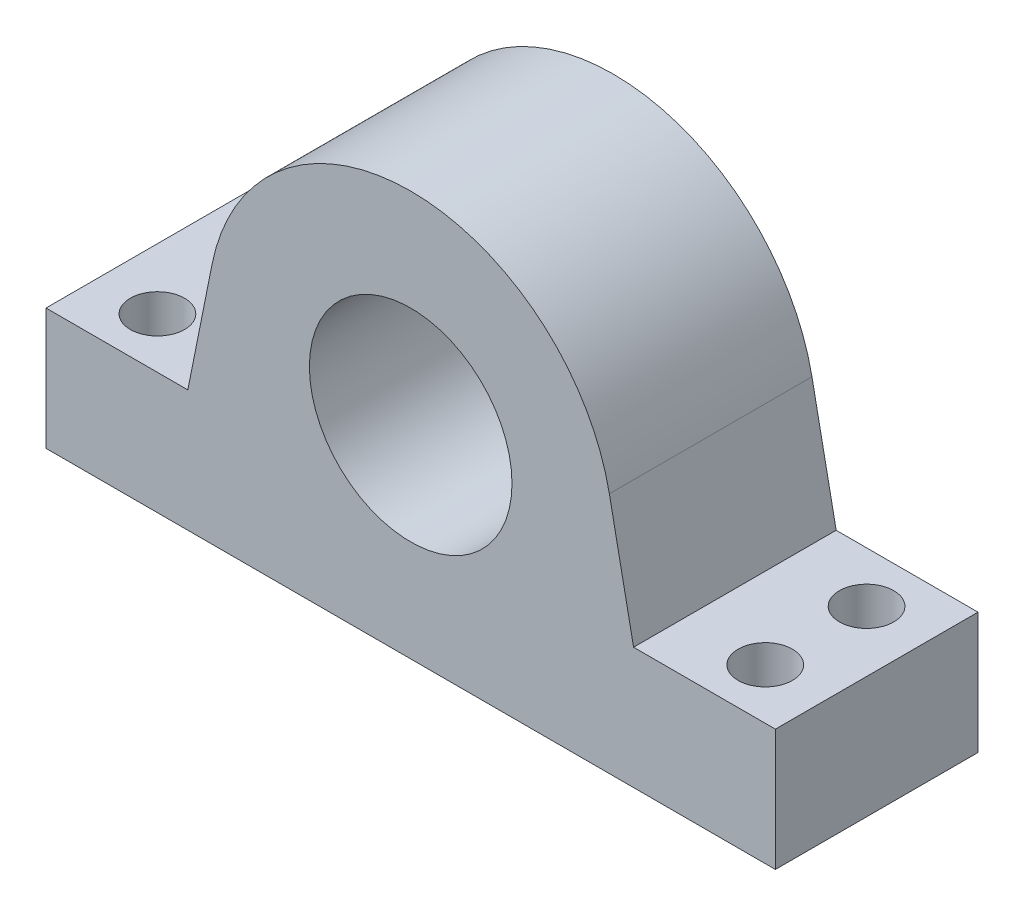
SolidWorks part; units mm, degrees
ref_plane "Front Plane" through (0, 0, 0) normal (0, 0, 1) x (1, 0, 0)
ref_plane "Top Plane" through (0, 0, 0) normal (0, 1, 0) x (1, 0, 0)
ref_plane "Right Plane" through (0, 0, 0) normal (1, 0, 0) x (0, 0, -1)
sketch "Sketch1" plane through (0, 0, 0) normal (0, 0, 1) x (1, 0, 0)
  line L0 (-12.4526, 2.4946) -> (-13.97, -5.08)
  line L1 (12.4526, 2.4946) -> (13.97, -5.08)
  line L2 (-13.97, -5.08) -> (-22.86, -5.08)
  line L3 (-22.86, -5.08) -> (-22.86, -12.7)
  line L4 (-22.86, -12.7) -> (22.86, -12.7)
  line L5 (22.86, -12.7) -> (22.86, -5.08)
  line L6 (22.86, -5.08) -> (13.97, -5.08)
  circle A0 centre (0, 0) radius 6.35
  arc A1 (12.4526, 2.4946) -> (-12.4526, 2.4946) centre (0, 0) ccw
  point P8 (0, 0)
  dimension "D1" = 12.7
  dimension "D6" = 12.7
  dimension "D2" = 7.62
  dimension "D3" = 45.72
  dimension "D4" = 12.7
  dimension "D5" = 8.89
extrude "Boss-Extrude1" add sketch "Sketch1" along normal mid plane 12.7
sketch "Sketch2" plane through (0, -5.08, 0) normal (0, 1, 0) x (1, 0, 0)
  circle A0 centre (-19.05, 3.175) radius 1.7018
  dimension "D1" = 3.4036
  dimension "D2" = 3.175
  dimension "D3" = 19.05
extrude "Cut-Extrude1" cut sketch "Sketch2" against normal through all
mirror "Mirror1" about plane through (0, 0, 0) normal (1, 0, 0) of "Cut-Extrude1" second plane through (0, 0, 0) second plane normal (0, 0, 1)
